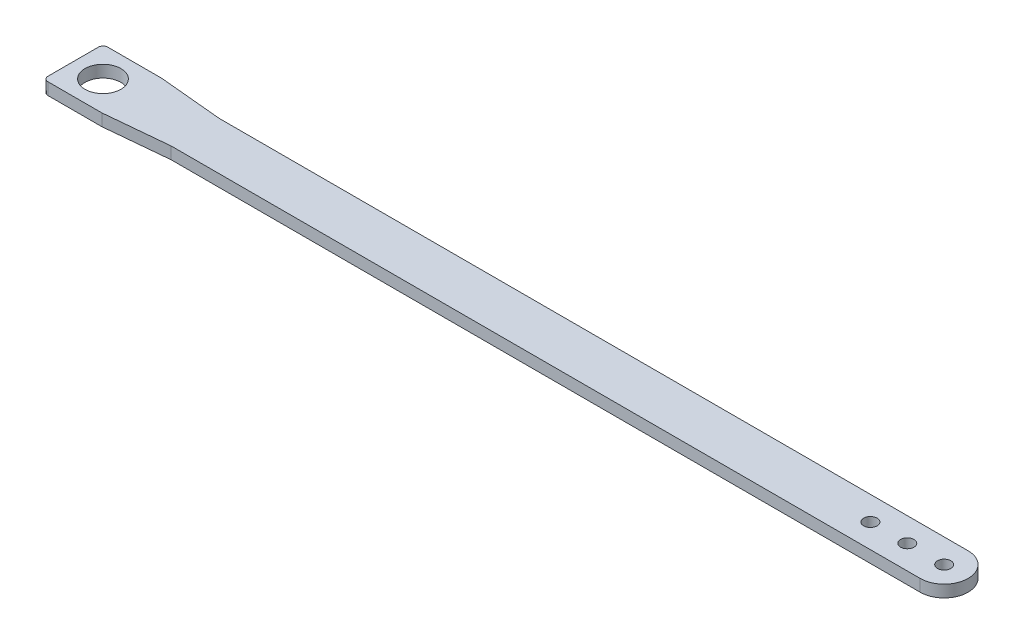
SolidWorks part; units mm, degrees
ref_plane "Front Plane" through (0, 0, 0) normal (0, 0, 1) x (1, 0, 0)
ref_plane "Top Plane" through (0, 0, 0) normal (0, 1, 0) x (1, 0, 0)
ref_plane "Right Plane" through (0, 0, 0) normal (1, 0, 0) x (0, 0, -1)
ref_plane "Plane1" through (0, 6.35, 0) normal (0, 1, 0) x (1, 0, 0)
sketch "Sketch1" plane through (0, 6.35, 0) normal (0, 1, 0) x (1, 0, 0)
  line L0 (187.7568, 6.985) -> (-187.7568, 6.985)
  line L1 (-187.7568, -5.715) -> (187.7568, -5.715)
  arc A0 (187.7568, -5.715) -> (187.7568, 6.985) centre (187.7568, 0.635) ccw
  arc A1 (-187.7568, 6.985) -> (-187.7568, -5.715) centre (-187.7568, 0.635) ccw
  circle A2 centre (187.7568, 0.635) radius 1.778
  circle A34 centre (-187.7568, 0.635) radius 1.778
  dimension "D2" = 3.556
  dimension "D1" = 12.7
extrude "Boss-Extrude1" add sketch "Sketch1" against normal blind 3.175
sketch "Sketch2" plane through (0, 6.35, 0) normal (0, 1, 0) x (1, 0, 0)
  line L5 (-41.5254, 17.6394) -> (-207.3143, 17.6394)
  line L6 (-41.5254, 17.6394) -> (-41.5254, -27.4758)
  line L7 (-41.5254, -27.4758) -> (-207.3143, -27.4758)
  line L8 (-207.3143, 17.6394) -> (-207.3143, -27.4758)
extrude "Cut-Extrude1" cut sketch "Sketch2" against normal blind 127
sketch "Sketch3" plane through (0, 6.35, 0) normal (0, 1, 0) x (1, 0, 0)
  line L0 (187.7568, 6.985) -> (-41.5254, 6.985) construction
  circle A0 centre (-35.2044, 0.635) radius 4.7625
  dimension "D1" = 9.525
  dimension "D2" = 6.35
extrude "Cut-Extrude2" cut sketch "Sketch3" against normal blind 127
sketch "Sketch4" plane through (0, 6.35, 0) normal (0, 1, 0) x (1, 0, 0)
  circle A0 centre (168.1988, 0.635) radius 1.778
  circle A1 centre (187.7568, 0.635) radius 1.778 construction
  circle A2 centre (177.9778, 0.635) radius 1.778
  dimension "D1" = 3.556
  dimension "D2" = 19.558
  dimension "D3" = 9.779
  dimension "D4" = 3.556
extrude "Cut-Extrude3" cut sketch "Sketch4" against normal blind 127
sketch "Sketch5" plane through (0, 6.35, 0) normal (0, 1, 0) x (1, 0, 0)
  line L0 (187.7568, 6.985) -> (-41.5254, 6.985) construction
  line L1 (-27.5558, 6.985) -> (-41.5254, 6.985)
  line L2 (-27.5558, 6.985) -> (-27.5558, 8.5725)
  line L3 (-27.5558, 8.5725) -> (-41.5254, 8.5725)
  line L5 (-41.5254, -5.715) -> (-41.5254, 6.985) construction
  line L6 (-41.5254, 8.5725) -> (-43.1129, 8.5725)
  line L7 (-41.5254, 6.985) -> (-41.5254, -5.715)
  line L8 (-41.5254, -7.3025) -> (-43.1129, -7.3025)
  line L9 (-43.1129, 8.5725) -> (-43.1129, -7.3025)
  line L10 (-41.5254, -5.715) -> (187.7568, -5.715) construction
  line L12 (-41.5254, -7.3025) -> (-27.5558, -7.3025)
  line L14 (-41.5254, -5.715) -> (-27.5558, -5.715)
  line L15 (-27.5558, -7.3025) -> (-27.5558, -5.715)
  dimension "D1" = 1.5875
  dimension "D2" = 1.5875
  dimension "D3" = 1.5875
extrude "Boss-Extrude2" add sketch "Sketch5" against normal up to surface (3.175 mm away) up to face at (168.1988, 3.175, 1.143)
fillet "Fillet3" radius 1.27 2 edges at (-43.1129, 4.7625, 7.3025) (-43.1129, 4.7625, -8.5725)
sketch "Sketch6" plane through (0, 6.35, 0) normal (0, 1, 0) x (1, 0, 0)
  line L0 (-27.5558, 8.5725) -> (-10.7714, 6.985)
  line L1 (187.7568, 6.985) -> (-27.5558, 6.985) construction
  line L2 (-10.7714, 6.985) -> (-27.5558, 6.985)
  line L3 (-27.5558, 6.985) -> (-27.5558, 8.5725)
  line L4 (-27.5558, -7.3025) -> (-10.7714, -5.715)
  line L5 (-27.5558, -5.715) -> (187.7568, -5.715) construction
  line L6 (-10.7714, -5.715) -> (-27.5558, -5.715)
  line L7 (-27.5558, -5.715) -> (-27.5558, -7.3025)
extrude "Boss-Extrude3" add sketch "Sketch6" against normal up to surface (3.175 mm away) up to face at (10.1203, 3.175, -0.635)
ref_plane "Plane2" through (0, 0, -0.635) normal (0, 0, 1) x (1, 0, 0)
